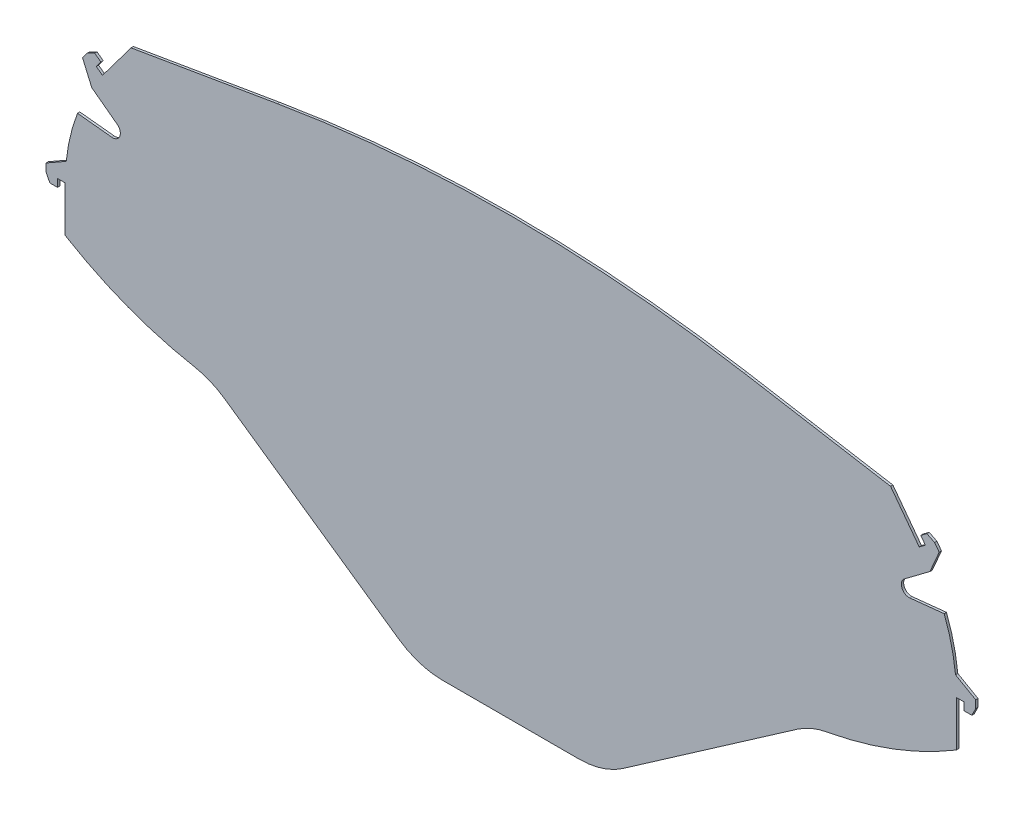
SolidWorks part; units mm, degrees
ref_plane "Front Plane" through (0, 0, 0) normal (0, 0, 1) x (1, 0, 0)
ref_plane "Top Plane" through (0, 0, 0) normal (0, 1, 0) x (1, 0, 0)
ref_plane "Right Plane" through (0, 0, 0) normal (1, 0, 0) x (0, 0, -1)
sketch "Sketch1" plane through (0, 0, 0) normal (0, 0, 1) x (1, 0, 0)
  line L0 (-24, -91.7648) -> (24, -91.7648)
  line L1 (0, 0) -> (0, -91.7648) construction
  line L2 (-10, 0) -> (-17, 10.2352)
  line L5 (-100.1804, -19.9556) -> (-60.7439, -13.2648)
  line L7 (-24, -91.7648) -> (-78.2662, -84.0567)
  line L8 (-17, 10.2352) -> (-26.9419, 9.1584)
  line L13 (-122.5, -58.7648) -> (122.5, -58.7648) construction
  line L14 (-60.7439, -13.2648) -> (-60.7439, -58.7648) construction
  line L15 (-113.5977, -28.7648) -> (-113.5977, -58.7648) construction
  line L16 (-10, 0) -> (10, 0)
  line L17 (10, 0) -> (17, 10.2352)
  line L18 (113.5977, -28.7648) -> (113.5977, -58.7648) construction
  line L19 (60.7439, -13.2648) -> (60.7439, -58.7648) construction
  line L20 (17, 10.2352) -> (26.9419, 9.1584)
  line L21 (24, -91.7648) -> (78.2662, -84.0567)
  line L22 (100.1804, -19.9556) -> (60.7439, -13.2648)
  line L23 (-17, 10.2352) -> (17, 10.2352) construction
  line L24 (0, 10.2352) -> (0, 0) construction
  arc A0 (-26.9419, 9.1584) -> (-43.4614, -1.4344) centre (-24.5729, -12.7137) ccw
  arc A1 (-43.4614, -1.4344) -> (-60.7439, -13.2648) centre (-64.9257, 11.383) cw
  arc A2 (-113.5977, -28.7648) -> (-100.1804, -19.9556) centre (-96.8349, -39.6739) cw
  arc A3 (-122.5, -58.7648) -> (-113.5977, -28.7648) centre (-67.5, -58.7648) cw
  arc A8 (-122.5, -58.7648) -> (-115.7111, -70.7648) centre (-108.5, -58.7648) ccw
  arc A9 (-115.7111, -70.7648) -> (-78.2662, -84.0567) centre (-64.2032, 14.9495) ccw
  arc A10 (115.7111, -70.7648) -> (78.2662, -84.0567) centre (64.2032, 14.9495) cw
  arc A11 (122.5, -58.7648) -> (115.7111, -70.7648) centre (108.5, -58.7648) cw
  arc A12 (122.5, -58.7648) -> (113.5977, -28.7648) centre (67.5, -58.7648) ccw
  arc A13 (113.5977, -28.7648) -> (100.1804, -19.9556) centre (96.8349, -39.6739) ccw
  arc A14 (43.4614, -1.4344) -> (60.7439, -13.2648) centre (64.9257, 11.383) ccw
  arc A15 (26.9419, 9.1584) -> (43.4614, -1.4344) centre (24.5729, -12.7137) cw
  dimension "D5" = 55
  dimension "D7" = 20
  dimension "D9" = 25
  dimension "D11" = 22
  dimension "D12" = 14
  dimension "D19" = 100
  dimension "D2" = 50.7439
  dimension "D3" = 102
  dimension "D4" = 10
  dimension "D6" = 14
  dimension "D8" = 40
  dimension "D10" = 58.7648
  dimension "D13" = 188.084
  dimension "D14" = 12.4
  dimension "D15" = 45.5
  dimension "D16" = 30
  dimension "D17" = 33
  dimension "D18" = 118.187
  dimension "D20" = 20
extrude "Main Shape" add sketch "Sketch1" along normal blind 0.6
sketch "Sketch2" plane through (0, 0, 0.6) normal (0, 0, 1) x (1, 0, 0)
  line L0 (0, 0) -> (0, -91.7648) construction
  line L1 (-24, -91.7648) -> (24, -91.7648) construction
  line L5 (-121, -58.7648) -> (-121, -56.7648)
  line L15 (-116, -58.7648) -> (-116, -70.5864)
  line L23 (113.5111, -43.4277) -> (119.6776, -41.3722) construction
  line L24 (113.5111, -43.4277) -> (106.4062, -22.1128) construction
  line L25 (110.3, -26.6648) -> (111.5, -28.2648)
  line L41 (-106.3, -29.6648) -> (-98.8487, -19.7297)
  line L42 (-60.7439, -13.2648) -> (-100.1804, -19.9556) construction
  line L43 (-98.8487, -19.7297) -> (-100.1804, -19.9556)
  line L44 (-116, -58.7648) -> (-118, -58.7648)
  line L45 (-118, -58.7648) -> (-118, -60.7648)
  line L46 (-118, -60.7648) -> (-120, -60.7648)
  line L47 (-120, -60.7648) -> (-121, -58.7648)
  line L48 (-121, -56.7648) -> (-115.7423, -53.7714)
  line L49 (-113.5111, -43.4277) -> (-106.4062, -22.1128) construction
  line L50 (-113.5111, -43.4277) -> (-119.6776, -41.3722) construction
  line L51 (-111.5, -28.2648) -> (-109.0898, -33.8141)
  line L52 (-108.3, -25.6648) -> (-110.3, -26.6648)
  line L53 (-106.7, -26.8648) -> (-108.3, -25.6648)
  line L54 (-107.9, -28.4648) -> (-106.7, -26.8648)
  line L55 (-106.3, -29.6648) -> (-107.9, -28.4648)
  line L56 (-110.3, -26.6648) -> (-111.5, -28.2648)
  line L57 (106.3, -29.6648) -> (107.9, -28.4648)
  line L58 (107.9, -28.4648) -> (106.7, -26.8648)
  line L59 (106.7, -26.8648) -> (108.3, -25.6648)
  line L60 (108.3, -25.6648) -> (110.3, -26.6648)
  line L61 (111.5, -28.2648) -> (109.0898, -33.8141)
  line L62 (121, -56.7648) -> (115.7423, -53.7714)
  line L63 (120, -60.7648) -> (121, -58.7648)
  line L64 (118, -60.7648) -> (120, -60.7648)
  line L65 (118, -58.7648) -> (118, -60.7648)
  line L66 (116, -58.7648) -> (118, -58.7648)
  line L67 (98.8487, -19.7297) -> (100.1804, -19.9556)
  line L68 (106.3, -29.6648) -> (98.8487, -19.7297)
  line L69 (116, -58.7648) -> (116, -70.5864)
  line L70 (121, -58.7648) -> (121, -56.7648)
  arc A9 (-106.3, -29.6648) -> (-116, -58.7648) centre (-67.5, -58.7648) ccw construction
  arc A11 (-113.5977, -28.7648) -> (-122.5, -58.7648) centre (-67.5, -58.7648) ccw construction
  arc A12 (-115.7423, -53.7714) -> (-109.0898, -33.8141) centre (-67.5, -58.7648) cw
  arc A13 (-107.5, -28.7648) -> (-117.5, -58.7648) centre (-67.5, -58.7648) ccw construction
  arc A14 (-105.1, -30.5648) -> (-114.5, -58.7648) centre (-67.5, -58.7648) ccw construction
  arc A15 (-105.1, -30.5648) -> (-107.5, -28.7648) centre (-106.3, -29.6648) ccw construction
  arc A16 (-117.5, -58.7648) -> (-114.5, -58.7648) centre (-116, -58.7648) ccw construction
  arc A18 (106.3, -29.6648) -> (116, -58.7648) centre (67.5, -58.7648) cw construction
  arc A19 (107.5, -28.7648) -> (117.5, -58.7648) centre (67.5, -58.7648) cw construction
  arc A21 (105.1, -30.5648) -> (114.5, -58.7648) centre (67.5, -58.7648) cw construction
  arc A22 (105.1, -30.5648) -> (107.5, -28.7648) centre (106.3, -29.6648) cw construction
  arc A23 (117.5, -58.7648) -> (114.5, -58.7648) centre (116, -58.7648) cw construction
  arc A24 (122.5, -58.7648) -> (116, -70.5864) centre (108.5, -58.7648) cw
  arc A25 (113.5977, -28.7648) -> (122.5, -58.7648) centre (67.5, -58.7648) cw
  arc A26 (100.1804, -19.9556) -> (113.5977, -28.7648) centre (96.8349, -39.6739) cw
  arc A33 (-122.5, -58.7648) -> (-115.7111, -70.7648) centre (-108.5, -58.7648) ccw construction
  arc A34 (-100.1804, -19.9556) -> (-113.5977, -28.7648) centre (-96.8349, -39.6739) ccw construction
  arc A35 (-100.1804, -19.9556) -> (-113.5977, -28.7648) centre (-96.8349, -39.6739) ccw
  arc A36 (-113.5977, -28.7648) -> (-122.5, -58.7648) centre (-67.5, -58.7648) ccw
  arc A37 (-122.5, -58.7648) -> (-116, -70.5864) centre (-108.5, -58.7648) ccw
  arc A38 (115.7423, -53.7714) -> (109.0898, -33.8141) centre (67.5, -58.7648) ccw
  point P24 (-113.5111, -43.4277)
  point P46 (113.5111, -43.4277)
  dimension "D1" = 1.5
  dimension "D2" = 5
  dimension "D3" = 2
  dimension "D7" = 5
  dimension "D4" = 2
  dimension "D5" = 2
  dimension "D6" = 2
  dimension "D8" = 5
extrude "Tabs" cut sketch "Sketch2" against normal through all both and the other way through all
sketch "Sketch5" plane through (0, 0, 0.6) normal (0, 0, 1) x (1, 0, 0)
  line L0 (-78.2662, -84.0567) -> (-24, -121.7648)
  line L1 (-24, -121.7648) -> (24, -121.7648)
  line L2 (24, -121.7648) -> (78.2662, -84.0567)
  line L3 (-78.2662, -84.0567) -> (-24, -91.7648) construction
  line L4 (24, -91.7648) -> (78.2662, -84.0567) construction
  line L5 (-24, -91.7648) -> (24, -91.7648) construction
  line L6 (24, -91.7648) -> (78.2662, -84.0567)
  line L7 (-24, -91.7648) -> (24, -91.7648)
  line L8 (-78.2662, -84.0567) -> (-24, -91.7648)
  dimension "D1" = 30
extrude "Chin guard" add sketch "Sketch5" against normal up to surface (0.6 mm away) up to face at (0, -39.2266, 0)
fillet "Fillet1" radius 20 4 edges at (-78.2662, -84.0567, 0.3) (78.2662, -84.0567, 0.3) (24, -121.7648, 0.3) (-24, -121.7648, 0.3)
sketch "Sketch6" plane through (0, 0, 0.6) normal (0, 0, 1) x (1, 0, 0)
  line L0 (-60.7439, -13.2648) -> (-98.8487, -19.7297) construction
  line L1 (98.8487, -19.7297) -> (60.7439, -13.2648) construction
  line L2 (-60.7439, -13.2648) -> (-60.7439, 16.7352)
  line L3 (-60.7439, 16.7352) -> (60.7439, 16.7352)
  line L4 (60.7439, 16.7352) -> (60.7439, -13.2648)
  arc A0 (-60.7439, -13.2648) -> (60.7439, -13.2648) centre (0, -371.2932) cw
  dimension "D1" = 30
extrude "Cut-Extrude1" cut sketch "Sketch6" against normal through all both and the other way through all
sketch "Sketch7" plane through (0, 0, 0.6) normal (0, 0, 1) x (1, 0, 0)
  line L0 (-109.0898, -33.8141) -> (-102.4491, -38.7946)
  line L1 (-106.3, -29.6648) -> (-107.9, -28.4648) construction
  line L2 (0, -0.33) -> (0, 0.33) construction
  line L3 (-103.8548, -42.384) -> (-112.8071, -41.4582)
  line L4 (103.8548, -42.384) -> (112.8071, -41.4582)
  line L5 (109.0898, -33.8141) -> (102.4491, -38.7946)
  arc A0 (-109.0898, -33.8141) -> (-115.7423, -53.7714) centre (-67.5, -58.7648) ccw construction
  arc A1 (-103.8548, -42.384) -> (-102.4491, -38.7946) centre (-103.6491, -40.3946) ccw
  arc A2 (-109.0898, -33.8141) -> (-112.8071, -41.4582) centre (-67.5, -58.7648) ccw
  arc A3 (109.0898, -33.8141) -> (112.8071, -41.4582) centre (67.5, -58.7648) cw
  arc A4 (103.8548, -42.384) -> (102.4491, -38.7946) centre (103.6491, -40.3946) cw
  dimension "D2" = 2
  dimension "D1" = 8.5
  dimension "D3" = 9
extrude "Cut-Extrude2" cut sketch "Sketch7" against normal through all both and the other way through all
